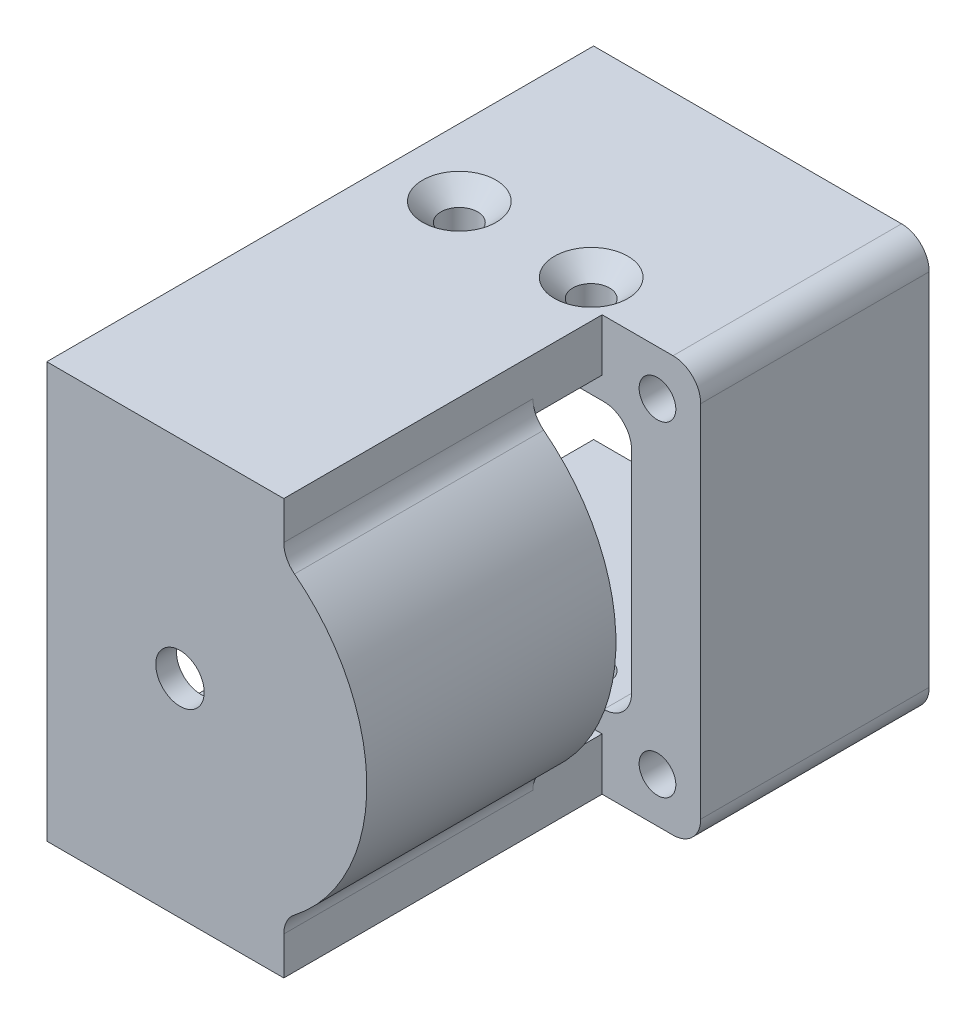
SolidWorks part; units mm, degrees
material "ABS"
ref_plane "Front Plane" through (0, 0, 0) normal (0, 0, 1) x (1, 0, 0)
ref_plane "Top Plane" through (0, 0, 0) normal (0, 1, 0) x (1, 0, 0)
ref_plane "Right Plane" through (0, 0, 0) normal (1, 0, 0) x (0, 0, -1)
sketch "Sketch1" plane through (0, 0, 0) normal (0, 0, 1) x (1, 0, 0)
  line L0 (-19.25, 19.25) -> (-19.25, 30)
  line L1 (-19.25, -19.25) -> (19.25, -19.25)
  line L3 (-19.25, 19.25) -> (19.25, 19.25)
  line L4 (19.25, -19.25) -> (19.25, 19.25)
  line L5 (-19.25, -19.25) -> (19.25, 19.25) construction
  line L6 (-19.25, 19.25) -> (19.25, -19.25) construction
  line L7 (-19.25, 30) -> (29.25, 30)
  line L8 (29.25, 30) -> (29.25, -30)
  line L9 (29.25, -30) -> (-19.25, -30)
  line L10 (-19.25, -30) -> (-19.25, -19.25)
  line L11 (0, 0) -> (19.25, 0) construction
  line L12 (19.25, 19.25) -> (29.25, 30) construction
  point P0 (0, 0)
  point P12 (23, 23.5)
  point P13 (23, -23.5)
  point P14 (0, 0)
  point P16 (24.25, 24.625)
  dimension "D1" = 38.5
  dimension "D2" = 38.5
  dimension "D3" = 60
  dimension "D4" = 10
  dimension "D5" = 23
  dimension "D6" = 6.5
extrude "Boss-Extrude1" add sketch "Sketch1" along normal mid plane 33.02
hole_wizard "M5 Clearance Hole1" positions "Sketch4" profile "Sketch5" hole size "M5" standard "ANSI Metric" end condition through all
sketch "Sketch4" plane through (0, 0, -16.51) normal (0, 0, -1) x (-1, 0, 0)
  point P4 (-23, -23.5)
  point P9 (-23, 23.5)
sketch "Sketch5" plane through (23, -23.5, -16.51) normal (1, 0, 0) x (0, 1, 0)
  line L0 (0, 0) -> (0, 33.02)
  line L1 (0, 33.02) -> (2.65, 33.02)
  line L2 (2.65, 33.02) -> (2.65, 0)
  line L5 (2.65, 0) -> (0, 0)
  line L11 (0, -6.35) -> (0, 107.95) construction
  dimension "Thru Hole Dia." = 5.3
  dimension "Thru Hole Depth" = 33.02
fillet "Fillet1" radius 4 4 edges at (29.25, -30, 0) (29.25, 30, 0) (19.25, -19.25, 0) (19.25, 19.25, 0)
sketch "Sketch6" plane through (0, 0, 16.51) normal (0, 0, 1) x (1, 0, 0)
  line L2 (-19.25, 22.5) -> (-19.25, 30)
  line L3 (-19.25, 30) -> (15, 30)
  line L4 (25.25, 30) -> (-19.25, 30) construction
  line L5 (15, 30) -> (15, 22.4499)
  line L6 (23, 28.1188) -> (19, 25.8094) construction
  line L7 (19, 25.8094) -> (19, 21.1906) construction
  line L8 (19, 21.1906) -> (23, 18.8812) construction
  line L9 (23, 18.8812) -> (27, 21.1906) construction
  line L10 (27, 21.1906) -> (27, 25.8094) construction
  line L11 (27, 25.8094) -> (23, 28.1188) construction
  line L12 (0, 0) -> (19.25, 0) construction
  line L13 (19.25, 15.25) -> (19.25, -15.25) construction
  line L15 (-19.25, -22.5) -> (-19.25, -30)
  line L16 (-19.25, -30) -> (15, -30)
  line L17 (15, -30) -> (15, -22.4499)
  line L18 (0, 22.5) -> (-19.25, 22.5)
  line L19 (0, -22.5) -> (-19.25, -22.5)
  arc A0 (0, -22.5) -> (0, 22.5) centre (0, 0) ccw
  circle A1 centre (23, 23.5) radius 4 construction
  arc A3 (15, -22.4499) -> (15, 22.4499) centre (0, 0) ccw
  dimension "D1" = 45
  dimension "D4" = 27
  dimension "D2" = 8
  dimension "D3" = 4
extrude "Boss-Extrude2" add sketch "Sketch6" along normal blind 43
sketch "Sketch7" plane through (29.25, 0, 0) normal (1, 0, 0) x (0, 0, -1)
  line L0 (-59.51, -22.4499) -> (-16.51, -22.4499) construction
  line L1 (-16.51, 22.4499) -> (-26.51, 22.4499)
  line L2 (-16.51, 22.4499) -> (-16.51, -22.4499)
  line L3 (-16.51, -22.4499) -> (-26.51, -22.4499)
  line L4 (-26.51, 22.4499) -> (-26.51, -22.4499)
  dimension "D1" = 10
extrude "Cut-Extrude1" cut sketch "Sketch7" against normal through all both and the other way through all
fillet "Fillet2" radius 4 2 edges at (15, -22.4499, 43.01) (15, 22.4499, 43.01)
sketch "Sketch8" plane through (0, 0, 59.51) normal (0, 0, 1) x (1, 0, 0)
  line L0 (-19.25, 22.5) -> (-19.25, -22.5)
  line L8 (0, -22.5) -> (-19.25, -22.5)
  line L9 (-19.25, -22.5) -> (-19.25, -30)
  line L10 (-19.25, -30) -> (15, -30)
  line L11 (15, -30) -> (15, -24.4949)
  line L12 (15, 24.4949) -> (15, 30)
  line L13 (15, 30) -> (-19.25, 30)
  line L14 (-19.25, 30) -> (-19.25, 22.5)
  line L15 (-19.25, 22.5) -> (0, 22.5)
  line L16 (0, -22.5) -> (-19.25, -22.5) construction
  line L17 (-19.25, -22.5) -> (-19.25, -30)
  line L18 (-19.25, -30) -> (15, -30)
  line L19 (15, -30) -> (15, -24.4949)
  line L20 (15, 24.4949) -> (15, 30)
  line L21 (15, 30) -> (-19.25, 30)
  line L22 (-19.25, 30) -> (-19.25, 22.5)
  line L23 (-19.25, 22.5) -> (0, 22.5) construction
  circle A0 centre (0, 0) radius 3.5
  arc A4 (0, -22.5) -> (0, 22.5) centre (0, 0) ccw
  arc A5 (16.5484, -21.3343) -> (15, -24.4949) centre (19, -24.4949) ccw
  arc A6 (16.5484, -21.3343) -> (16.5484, 21.3343) centre (0, 0) ccw
  arc A7 (15, 24.4949) -> (16.5484, 21.3343) centre (19, 24.4949) ccw
  arc A8 (0, -22.5) -> (0, 22.5) centre (0, 0) ccw construction
  arc A9 (16.5484, -21.3343) -> (15, -24.4949) centre (19, -24.4949) ccw
  arc A10 (16.5484, -21.3343) -> (16.5484, 21.3343) centre (0, 0) ccw
  arc A11 (15, 24.4949) -> (16.5484, 21.3343) centre (19, 24.4949) ccw
  dimension "D2" = 7
  dimension "D1" = 0
extrude "Boss-Extrude3" add sketch "Sketch8" along normal blind 3
sketch "Sketch9" plane through (0, 30, 0) normal (0, 1, 0) x (1, 0, 0)
  line L0 (25.25, -16.51) -> (15, -16.51) construction
  line L1 (-19.05, -16.51) -> (19.05, -16.51) construction
  line L2 (-19.05, -16.51) -> (-19.05, -8.7225) construction
  line L3 (-19.05, -8.7225) -> (19.05, -8.7225) construction
  line L4 (19.05, -16.51) -> (19.05, -8.7225) construction
  line L5 (-19.05, -16.51) -> (19.05, -8.7225) construction
  line L6 (-19.05, -8.7225) -> (19.05, -16.51) construction
  line L7 (-19.25, -62.51) -> (-19.25, 16.51) construction
  line L8 (0, -12.6163) -> (0, -8.7225) construction
  point P0 (0, -12.6162)
  point P11 (-9.525, -12.6163)
  point P12 (9.525, -12.6163)
  dimension "D1" = 7.7875
  dimension "D2" = 38.1
  dimension "D3" = 0.2
  dimension "D4" = 19.05
hole_wizard "CSK for M5 Flat Head Machine Screw1" positions "Sketch10" profile "Sketch11" countersink size "M5" standard "ANSI Metric"
sketch "Sketch10" plane through (0, 30, 0) normal (0, 1, 0) x (1, 0, 0)
  point P0 (-9.525, -12.6163)
  point P3 (9.525, -12.6163)
sketch "Sketch11" plane through (-9.525, 30, 12.6163) normal (1, 0, 0) x (0, 0, 1)
  line L0 (0, 0) -> (0, 10.75)
  line L1 (0, 10.75) -> (2.65, 10.75)
  line L2 (2.65, 10.75) -> (2.65, 2.65)
  line L3 (2.65, 2.65) -> (5.3, 0)
  line L5 (5.3, 0) -> (0, 0)
  line L6 (-2.65, 2.65) -> (-5.3, 0) construction
  line L11 (0, -6.35) -> (0, 107.95) construction
  dimension "Thru Hole Dia." = 5.3
  dimension "Thru Hole Depth" = 10.75
  dimension "Near C'Sink Dia." = 10.6
  dimension "Near C'Sink Angle" = 90
mirror "Mirror1" about plane through (0, 0, 0) normal (0, 1, 0) of "CSK for M5 Flat Head Machine Screw1"
equation "\"D1@Boss-Extrude1\"=1.3in"
equation "\"D4@Sketch9\"=0.75in"
